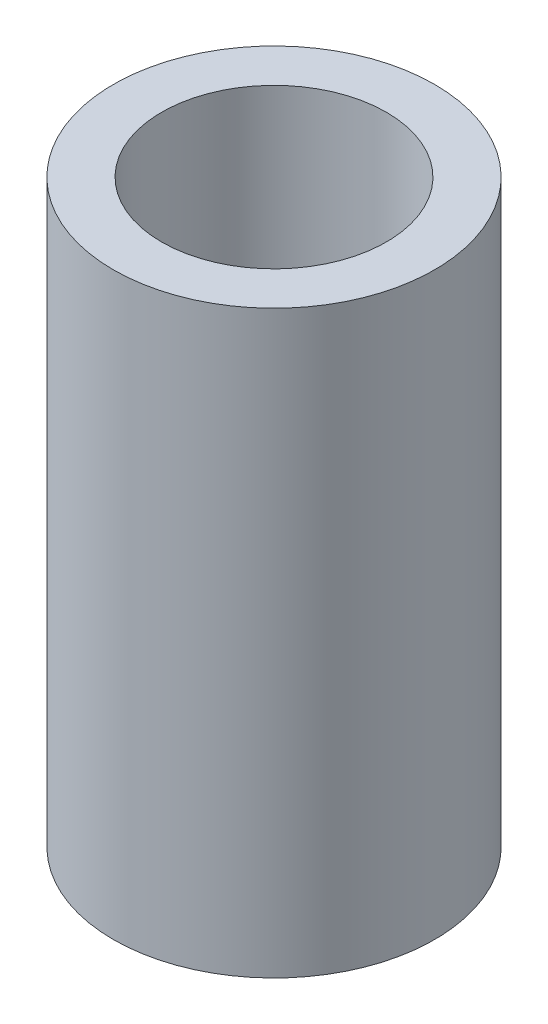
SolidWorks part; units mm, degrees
material "Custom Plastic"
ref_plane "X-Y Datum" through (0, 0, 0) normal (0, 0, 1) x (1, 0, 0)
ref_plane "X-Z Datum" through (0, 0, 0) normal (0, 1, 0) x (1, 0, 0)
ref_plane "Y-Z Datum" through (0, 0, 0) normal (1, 0, 0) x (0, 0, -1)
sketch "Sketch1" plane through (0, 0, 0) normal (0, 1, 0) x (1, 0, 0)
  circle A0 centre (0, 0) radius 2
  circle A1 centre (0, 0) radius 2.8575
  dimension "D1" = 4
  dimension "D2" = 5.715
extrude "Boss-Extrude1" add sketch "Sketch1" against normal blind 10.32
